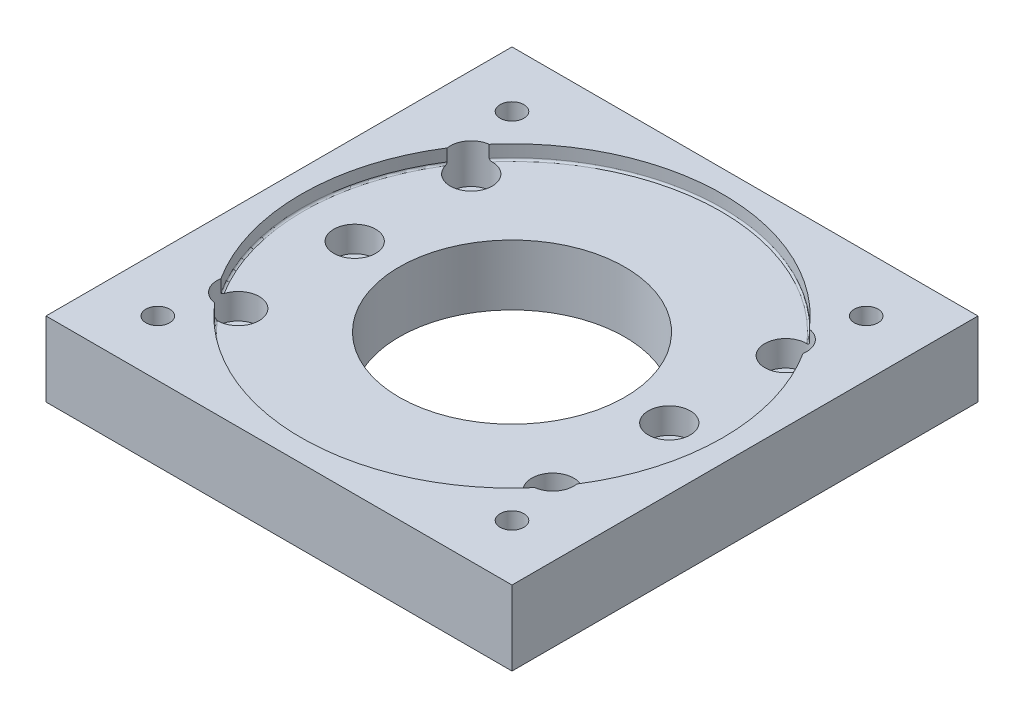
SolidWorks part; units mm, degrees
material "Low Carbon Steel"
ref_plane "Front Plane" through (0, 0, 0) normal (0, 0, 1) x (1, 0, 0)
ref_plane "Top Plane" through (0, 0, 0) normal (0, 1, 0) x (1, 0, 0)
ref_plane "Right Plane" through (0, 0, 0) normal (1, 0, 0) x (0, 0, -1)
sketch "Sketch1" plane through (0, 0, 0) normal (0, 1, 0) x (1, 0, 0)
  line L0 (-100, -100) -> (100, 100) construction
  line L1 (-100, 100) -> (100, 100)
  line L2 (-100, 100) -> (-100, -100)
  line L3 (-100, -100) -> (100, -100)
  line L4 (100, 100) -> (100, -100)
  dimension "D1" = 200
  dimension "D2" = 200
extrude "Boss-Extrude1" add sketch "Sketch1" along normal mid plane 38.1
sketch "Sketch2" plane through (0, 0, 100) normal (0, 0, 1) x (1, 0, 0)
  line L0 (100, 19.05) -> (100, -19.05) construction
  line L1 (-100, 19.05) -> (100, 19.05)
  line L2 (-100, 19.05) -> (-100, 16)
  line L3 (-100, 16) -> (100, 16)
  line L4 (100, 19.05) -> (100, 16)
  line L7 (-100, -19.05) -> (100, -19.05)
  line L8 (-100, -19.05) -> (-100, -16)
  line L9 (-100, -16) -> (100, -16)
  line L10 (100, -19.05) -> (100, -16)
  dimension "D1" = 32
  dimension "D2" = 3.05
extrude "Cut-Extrude1" cut sketch "Sketch2" against normal through all
sketch "Sketch3" plane through (0, 16, 0) normal (0, 1, 0) x (1, 0, 0)
  circle A0 centre (0, 0) radius 90.5
  dimension "D1" = 181
extrude "Cut-Extrude2" cut sketch "Sketch3" against normal blind 6
hole_wizard "M12 Tapped Hole1" positions "Sketch5" profile "Sketch4" tap size "M12" standard "Peddi DIN"
sketch "Sketch5" plane through (0, 16, 0) normal (0, 1, 0) x (1, 0, 0)
  line L0 (-76.014, 76.014) -> (76.014, 76.014) construction
  line L1 (76.014, 76.014) -> (76.014, -76.014) construction
  line L2 (76.014, -76.014) -> (-76.014, -76.014) construction
  line L3 (-76.014, -76.014) -> (-76.014, 76.014) construction
  circle A0 centre (0, 0) radius 107.5 construction
  point P0 (-76.014, 76.014)
  point P2 (76.014, 76.014)
  point P4 (76.014, -76.014)
  point P6 (-76.014, -76.014)
  dimension "D1" = 215
sketch "Sketch4" plane through (-76.014, 16, -76.014) normal (1, 0, 0) x (0, 0, 1)
  line L0 (0, 0) -> (0, 35.8144)
  line L1 (0, 35.8144) -> (5.1, 32.75)
  line L2 (5.1, 32.75) -> (5.1, 0)
  line L5 (5.1, 0) -> (0, 0)
  line L10 (0, 35.8144) -> (-5.1, 32.75) construction
  line L11 (0, -6.35) -> (0, 107.95) construction
  dimension "Tap Drill Dia." = 10.2
  dimension "Tap Drill Depth" = 32.75
  dimension "Drill Angle" = 118
cosmetic thread "Hole Thread1" parameters "D1"=30, "D2"=12
cosmetic thread "Hole Thread2" parameters "D1"=30, "D2"=12
cosmetic thread "Hole Thread3" parameters "D1"=30, "D2"=12
cosmetic thread "Hole Thread4" parameters "D1"=30, "D2"=12
sketch "Sketch6" plane through (0, 10, 0) normal (0, 1, 0) x (1, 0, 0)
  circle A0 centre (0, 0) radius 48.4187
  dimension "D1" = 96.8375
extrude "Cut-Extrude3" cut sketch "Sketch6" against normal through all contours A0
fillet "Fillet1" radius 0.7937 1 edges at (0, 10, 90.5)
hole_wizard "CBORE for M10 Hex Socket Head Cap Screw1" positions "Sketch8" profile "Sketch7" counterbore size "M10" standard "Peddi DIN" end condition through all
sketch "Sketch8" plane through (0, 16, 0) normal (0, 1, 0) x (1, 0, 0)
  line L0 (67.5, -50) -> (67.5, 50) construction
  line L1 (67.5, 50) -> (-67.5, 50) construction
  line L2 (-67.5, 50) -> (-67.5, -50) construction
  line L3 (0, 0) -> (0, 50) construction
  circle A0 centre (0, 0) radius 48.4187 construction
  point P0 (-67.5, -50)
  point P2 (-67.5, 0)
  point P4 (-67.5, 50)
  point P6 (67.5, 50)
  point P8 (67.5, 0)
  point P10 (67.5, -50)
  dimension "D1" = 50
  dimension "D2" = 100
  dimension "D3" = 135
sketch "Sketch7" plane through (-67.5, 16, 50) normal (1, 0, 0) x (0, 0, 1)
  line L0 (0, 0) -> (0, 32)
  line L1 (0, 32) -> (5.5, 32)
  line L3 (5.5, 32) -> (5.5, 17)
  line L4 (5.5, 17) -> (9, 17)
  line L5 (9, 17) -> (9, 0)
  line L7 (9, 0) -> (0, 0)
  line L11 (0, -6.35) -> (0, 107.95) construction
  dimension "Thru Hole Dia." = 11
  dimension "Thru Hole Depth" = 32
  dimension "C'Bore Dia." = 18
  dimension "C'Bore Depth" = 17
other "Freeze***"
